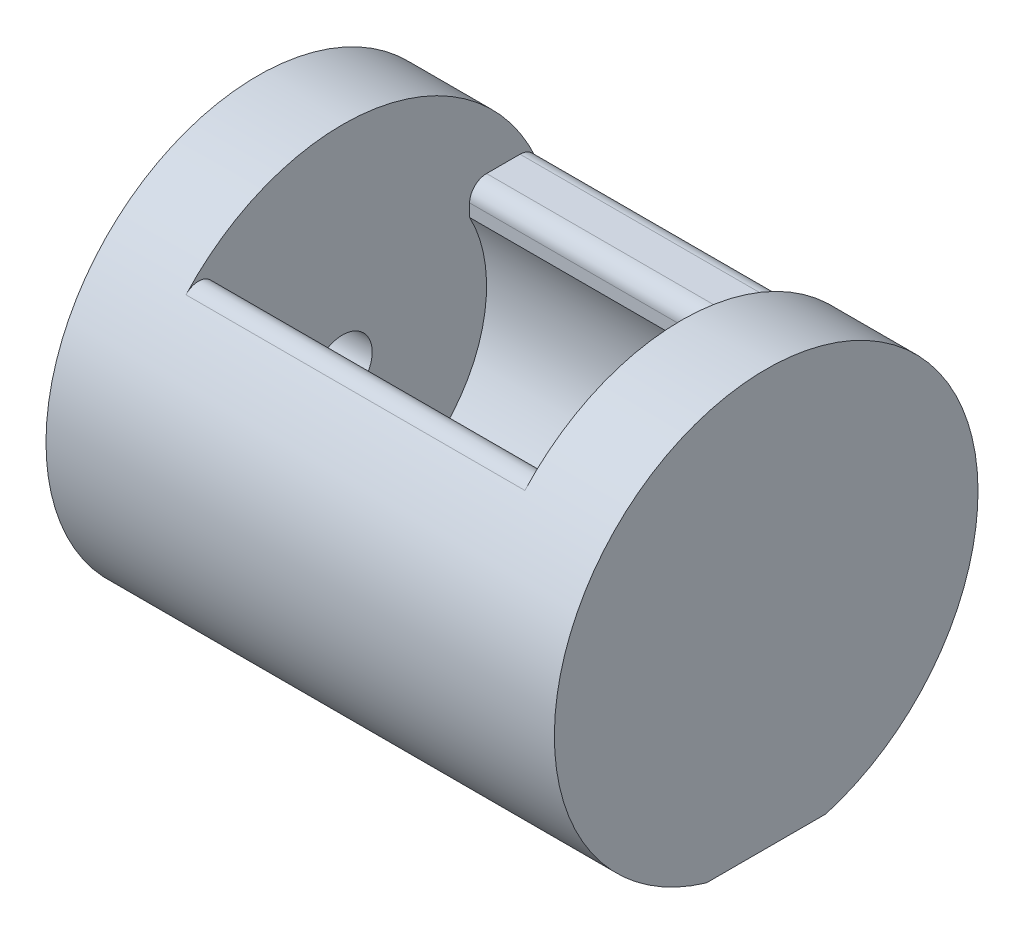
SolidWorks part; units mm, degrees
ref_plane "Front Plane" through (0, 0, 0) normal (0, 0, 1) x (1, 0, 0)
ref_plane "Top Plane" through (0, 0, 0) normal (0, 1, 0) x (1, 0, 0)
ref_plane "Right Plane" through (0, 0, 0) normal (1, 0, 0) x (0, 0, -1)
sketch "Sketch2" plane through (0, 0, 0) normal (1, 0, 0) x (0, 0, -1)
  circle A0 centre (0, 0) radius 25
extrude "Boss-Extrude1" add sketch "Sketch2" along normal blind 60 contours A0
sketch "Sketch4" plane through (0, 0, 0) normal (0, 1, 0) x (1, 0, 0)
  line L0 (10, 0) -> (10, 15)
  line L2 (10, 15) -> (50, 15)
  line L3 (10, 0) -> (10, -15)
  line L4 (10, -15) -> (50, -15)
  line L5 (50, -15) -> (50, 15)
  dimension "D1" = 10
  dimension "D3" = 15
  dimension "D4" = 30
extrude "Cut-Extrude3" cut sketch "Sketch4" along normal blind 30 contours L0 L2 L5 L4 L3
ref_plane "Plane1" through (30, 0, 0) normal (1, 0, 0) x (0, 0, -1)
sketch "Sketch5" plane through (30, 0, 0) normal (1, 0, 0) x (0, 0, -1)
  circle A0 centre (0, 0) radius 17
extrude "Cut-Extrude4" cut sketch "Sketch5" against normal blind 20 and the other way blind 20
fillet "Fillet3" radius 2 2 edges at (30, 20, 15) (30, 20, -15)
sketch "Sketch6" plane through (0, 0, 0) normal (1, 0, 0) x (0, 0, -1)
  circle A0 centre (0, 0) radius 3.5
  point P4 (0, 0)
  point P8 (8.5, 0)
extrude "Cut-Extrude5" cut sketch "Sketch6" along normal blind 20
sketch "Sketch7" plane through (0, 0, 0) normal (1, 0, 0) x (0, 0, -1)
  line L1 (-8.5, -0.45) -> (-8.5, 0)
  line L2 (8.5, 0) -> (8.5, -17.5)
  line L3 (8.5, -17.5) -> (-8.5, -17.5)
  line L4 (-8.5, -17.5) -> (-8.5, -0.45)
  arc A0 (-8.5, 0) -> (8.5, 0) centre (0, 0) cw
  point P5 (0, 0)
extrude "Cut-Extrude7" cut sketch "Sketch7" along normal blind 3 contours L2 L3 L4 L1 A0
sketch "Sketch8" plane through (0, 0, 0) normal (1, 0, 0) x (0, 0, -1)
  line L0 (0, -25) -> (-19.6127, -25)
  line L1 (-19.6127, -25) -> (-19.6127, -23.9862)
  line L2 (-19.6127, -23.9862) -> (13.394, -23.9862)
  line L3 (13.394, -23.9862) -> (13.394, -25)
  line L4 (13.394, -25) -> (0, -25)
  circle A0 centre (0, 0) radius 25 construction
extrude "Cut-Extrude8" cut sketch "Sketch8" along normal through all contours L2 L3 L4 L0 L1
sketch "Sketch9" plane through (0, 0, 0) normal (0, 0, 1) x (1, 0, 0)
  line L12 (10, 17.4919) -> (50, 17.4919)
  line L13 (50, 25) -> (50, 16.8391) construction
  line L14 (50, 17.4919) -> (10, 17.4919) construction
  line L15 (50, 17.4919) -> (50, 11.4919)
  line L16 (50, 11.4919) -> (10, 11.4919)
  line L17 (10, 11.4919) -> (10, 17.4919)
extrude "Cut-Extrude9" cut sketch "Sketch9" against normal blind 30
fillet "Fillet5" radius 2 2 edges at (30, 11.4919, -15) (30, 11.4919, -22.2022)
